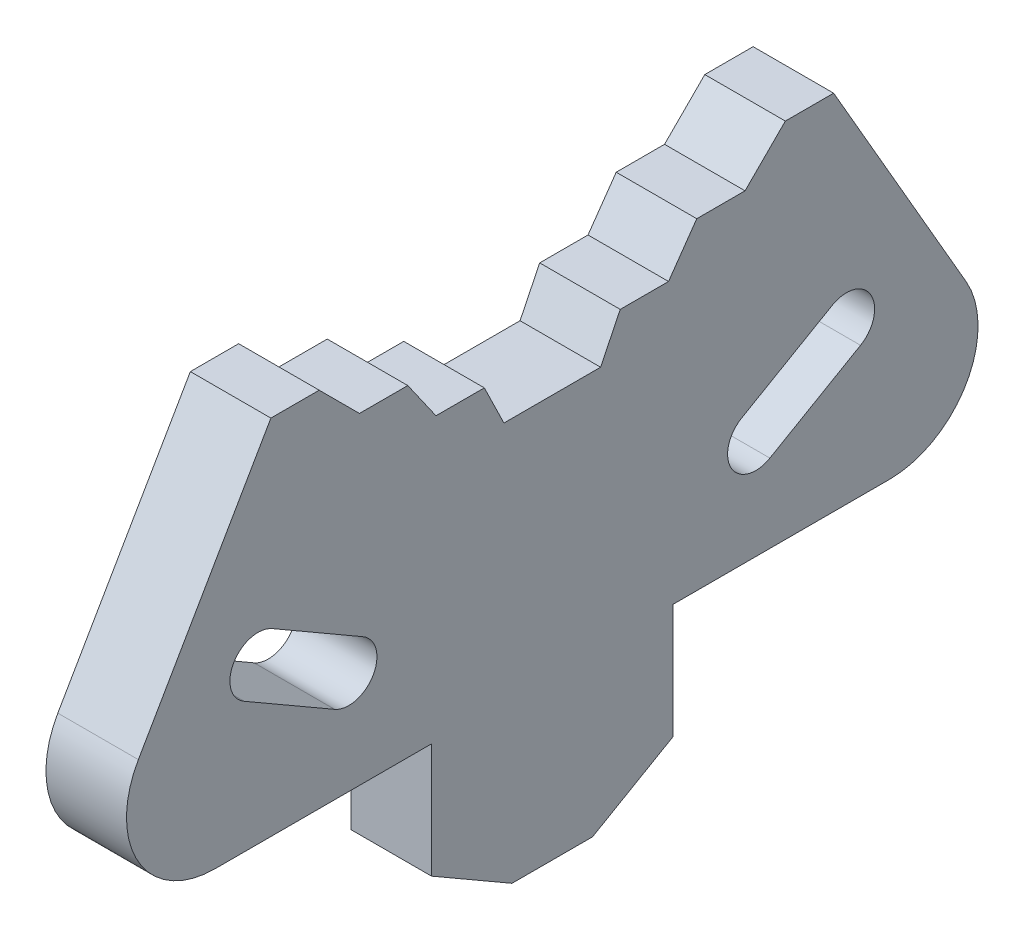
SolidWorks part; units mm, degrees
material "Сталь"
ref_plane "Спереди" through (0, 0, 0) normal (0, 0, 1) x (1, 0, 0)
ref_plane "Сверху" through (0, 0, 0) normal (0, 1, 0) x (1, 0, 0)
ref_plane "Справа" through (0, 0, 0) normal (1, 0, 0) x (0, 0, -1)
sketch "Эскиз1" plane through (0, 0, 0) normal (1, 0, 0) x (0, 0, -1)
  line L0 (0, 0) -> (41.8679, 0)
  line L1 (51.3942, 16.5) -> (34.9397, 45)
  line L2 (34.9397, 45) -> (28.9397, 45)
  line L3 (28.9397, 45) -> (23.9397, 40)
  line L4 (23.9397, 40) -> (17.9397, 40)
  line L5 (17.9397, 40) -> (14.4387, 35)
  line L6 (14.4387, 35) -> (8.4387, 35)
  line L7 (8.4387, 35) -> (6, 30)
  line L8 (6, 30) -> (0, 30)
  line L9 (0, 30) -> (0, 0)
  line L10 (25.2691, 12.75) -> (36.5274, 19.25) construction
  line L11 (23.5191, 15.7811) -> (34.7774, 22.2811)
  line L12 (27.0191, 9.7189) -> (38.2774, 16.2189)
  line L13 (39.5585, 21) -> (54.6058, -5.0627) construction
  arc A0 (41.8679, 0) -> (51.3942, 16.5) centre (41.8679, 11) ccw
  arc A1 (23.5191, 15.7811) -> (27.0191, 9.7189) centre (25.2691, 12.75) ccw
  arc A2 (38.2774, 16.2189) -> (34.7774, 22.2811) centre (36.5274, 19.25) ccw
  point P15 (30.8982, 16)
  dimension "D1" = 11
  dimension "D2" = 7
  dimension "D3" = 20
  dimension "D4" = 60
  dimension "D16" = 16
  dimension "D5" = 26
  dimension "D6" = 35
  dimension "D7" = 45
  dimension "D8" = 30
  dimension "D9" = 6
  dimension "D10" = 35
  dimension "D11" = 40
  dimension "D12" = 45
  dimension "D13" = 6
  dimension "D14" = 6
  dimension "D15" = 6
  dimension "D17" = 8
extrude "Бобышка-Вытянуть1" add sketch "Эскиз1" along normal blind 10
mirror "Зеркальное отражение1" about plane through (10, 30, 0) normal (0, 0, -1) of bodies 105
sketch "Эскиз2" plane through (10, 0, 0) normal (1, 0, 0) x (0, 0, -1)
  line L0 (0, 0) -> (0, -46.6289) construction
  line L1 (-41.8679, 0) -> (41.8679, 0) construction
  line L2 (-15, -20) -> (15, -20)
  line L3 (-15, -20) -> (-15, 0)
  line L4 (-15, 0) -> (15, 0)
  line L5 (15, -20) -> (15, 0)
  line L6 (-15, -20) -> (15, 0) construction
  line L7 (-15, 0) -> (15, -20) construction
  point P3 (0, -10)
  dimension "D1" = 30
  dimension "D2" = 20
extrude "Бобышка-Вытянуть2" add sketch "Эскиз2" against normal up to surface (10 mm away) up to face at (0, 31.5278, 0)
chamfer "Фаска1" distance 10 angle 30 1 edges at (5, -20, 15)
chamfer "Фаска2" distance 10 angle 30 1 edges at (5, -20, -15)
